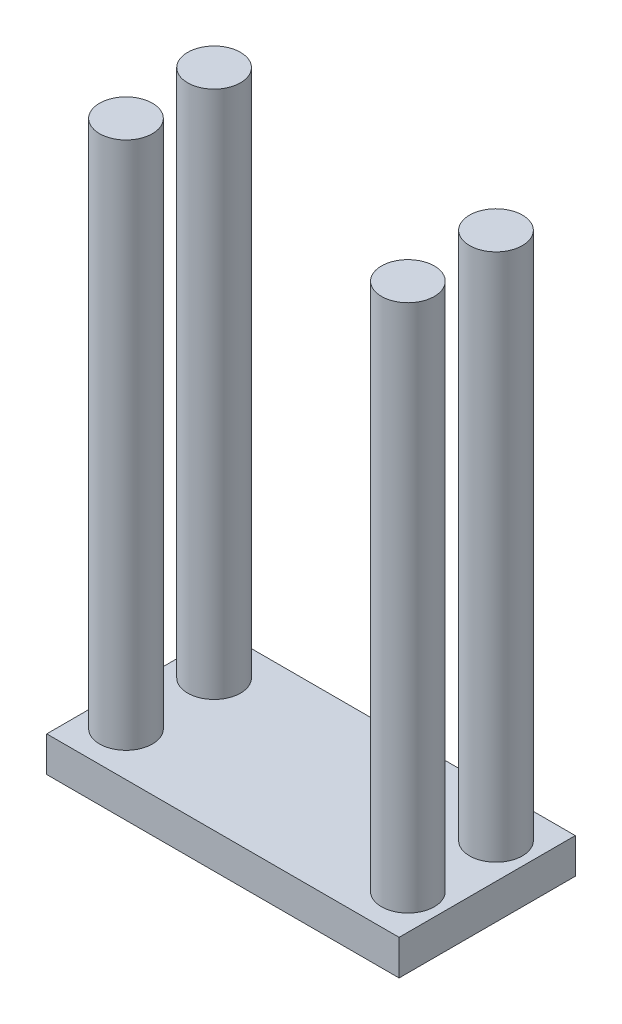
SolidWorks part; units mm, degrees
ref_plane "Front" through (0, 0, 0) normal (0, 0, 1) x (1, 0, 0)
ref_plane "Top" through (0, 0, 0) normal (0, 1, 0) x (1, 0, 0)
ref_plane "Right" through (0, 0, 0) normal (1, 0, 0) x (0, 0, -1)
sketch "草图1" plane through (0, 0, 0) normal (0, 1, 0) x (1, 0, 0)
  line L0 (-10, 0) -> (10, 0) construction
  line L1 (-10, 2.5) -> (10, 2.5)
  line L2 (-10, 2.5) -> (-10, -2.5)
  line L3 (-10, -2.5) -> (10, -2.5)
  line L4 (10, 2.5) -> (10, -2.5)
  line L5 (-10, 2.5) -> (10, -2.5) construction
  line L6 (-10, -2.5) -> (10, 2.5) construction
  point P0 (0, 0)
  dimension "D1" = 5
  dimension "D2" = 20
extrude "凸台-拉伸2" add sketch "草图1" against normal blind 2
ref_plane "基准面3" through (0, 0, 0) normal (0, 1, 0) x (1, 0, 0)
sketch "草图4" plane through (0, 0, 0) normal (0, 1, 0) x (1, 0, 0)
  line L0 (-10, 0) -> (10, 0) construction
  line L1 (-10, 2.5) -> (-10, -2.5) construction
  line L2 (10, -2.5) -> (10, 2.5) construction
  line L3 (0, -2.5) -> (0, 2.5) construction
  line L4 (-10, -2.5) -> (10, -2.5) construction
  line L5 (10, 2.5) -> (-10, 2.5) construction
  circle A0 centre (-8, 0) radius 1.5
  circle A1 centre (8, 0) radius 1.5
  dimension "D1" = 8
extrude "凸台-拉伸3" add sketch "草图4" along normal blind 30
ref_plane "基准面4" through (0, 0, -2.5) normal (0, 0, -1) x (-1, 0, 0)
mirror "镜向1" about plane through (0, 0, -2.5) normal (0, 0, -1) of "凸台-拉伸2", "凸台-拉伸3"
